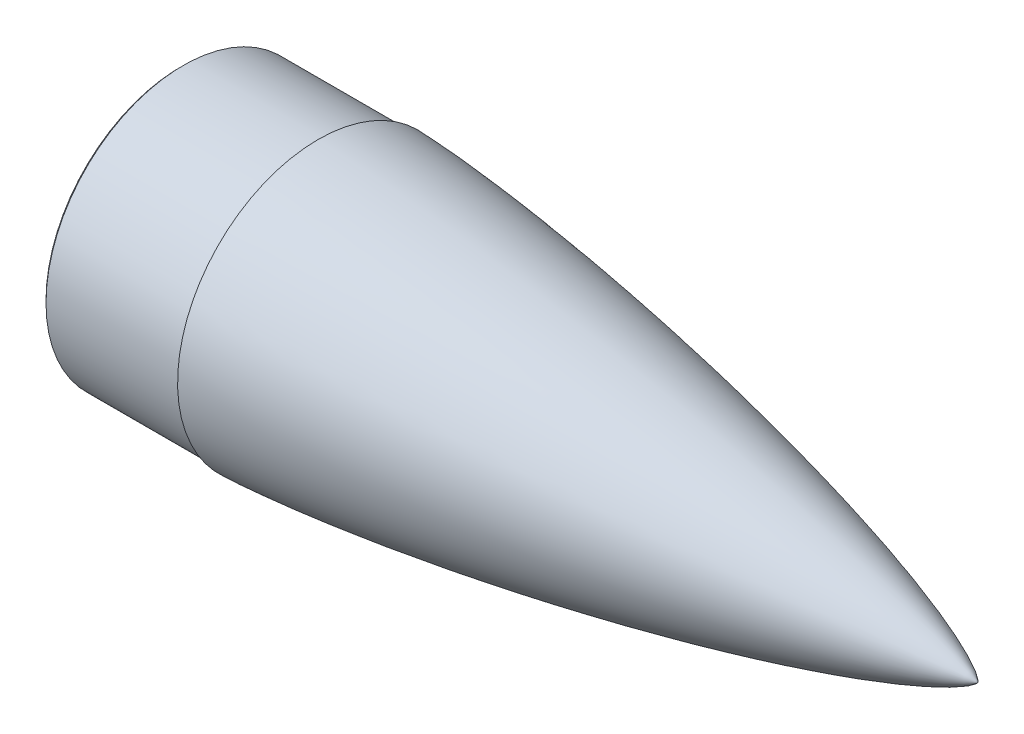
SolidWorks part; units mm, degrees
material "Plain Carbon Steel"
ref_plane "Front Plane" through (0, 0, 0) normal (0, 0, 1) x (1, 0, 0)
ref_plane "Top Plane" through (0, 0, 0) normal (0, 1, 0) x (1, 0, 0)
ref_plane "Right Plane" through (0, 0, 0) normal (1, 0, 0) x (0, 0, -1)
ref_axis "Axis1" through (46.9179, 0, 0) along (-1, 0, 0)
sketch "Sketch10" plane through (0, 0, 0) normal (0, 0, 1) x (1, 0, 0)
  line L1 (-1.0327, 0) -> (486.9547, 0) construction
  line L2 (11.1125, 81.9998) -> (11.1125, 67.4998)
  line L3 (11.1125, 81.9998) -> (-84.6045, 81.9998)
  line L4 (408.9673, 0) -> (368.9673, 0)
  line L5 (-84.6045, 81.9998) -> (-84.6045, 84.9998)
  line L6 (-84.6045, 84.9998) -> (0.3953, 84.9998)
  line L7 (0.3953, 84.9998) -> (0.3953, 86.9998)
  line L8 (11.1125, 67.4998) -> (129.3045, 67.4998)
  spline S0 degree 4 poles (408.9673, 0) (408.9649, 0.0135) (408.958, 0.0399) (408.9365, 0.0905) (408.8922, 0.1741) (408.8263, 0.2756) (408.7217, 0.4158) (408.5611, 0.6051) (408.3056, 0.8724) (407.8697, 1.2753) (407.121, 1.8851) (405.8038, 2.8259) (403.4624, 4.2872) (399.3253, 6.5318) (392.4811, 9.7589) (380.6621, 14.628) (363.6372, 20.7117) (342.2152, 27.4765) (317.4285, 34.4976) (291.8793, 41.1048) (266.2105, 47.229) (240.4455, 52.9334) (214.5989, 58.2554) (188.6809, 63.2176) (165.9462, 67.2533) (146.422, 70.4938) (130.1279, 73.0449) (117.0786, 74.9942) (104.0155, 76.8485) (92.5733, 78.3845) (82.7571, 79.6356) (74.5713, 80.6322) (68.0193, 81.4008) (61.4637, 82.1394) (54.9047, 82.8464) (48.3422, 83.5199) (41.7761, 84.1578) (36.0275, 84.6822) (31.0979, 85.1052) (26.9883, 85.4387) (23.6997, 85.6932) (20.0858, 85.9584) (16.7199, 86.189) (13.6021, 86.387) (10.7327, 86.5546) (8.4366, 86.6787) (6.14, 86.7922) (4.1299, 86.8793) (2.4065, 86.9446) (1.2573, 86.979) (0.6827, 86.9949) (0.3953, 86.9998) knots 0 0 0 0 0 0.00013 0.00026 0.00052 0.0009 0.00128 0.001925 0.002882 0.004418 0.006927 0.011111 0.018279 0.030673 0.051704 0.083102 0.139909 0.202703 0.265496 0.32829 0.391083 0.453877 0.516671 0.579464 0.642258 0.673655 0.705051 0.736448 0.767845 0.799242 0.81494 0.830639 0.846337 0.862036 0.877734 0.893432 0.909131 0.924829 0.932678 0.940527 0.948377 0.956226 0.967169 0.972641 0.978113 0.983585 0.989056 0.994528 0.997264 1 1 1 1 1 construction
  spline S1 degree 4 poles (408.9673, 0) (408.9649, 0.0135) (408.958, 0.0399) (408.9365, 0.0905) (408.8922, 0.1741) (408.8263, 0.2756) (408.7217, 0.4158) (408.5611, 0.6051) (408.3056, 0.8724) (407.8697, 1.2753) (407.121, 1.8851) (405.8038, 2.8259) (403.4624, 4.2872) (399.3253, 6.5318) (392.4811, 9.7589) (380.6621, 14.628) (363.6372, 20.7117) (342.2152, 27.4765) (317.4285, 34.4976) (291.8793, 41.1048) (266.2105, 47.229) (240.4455, 52.9334) (214.5989, 58.2554) (188.6809, 63.2176) (165.9462, 67.2533) (146.422, 70.4938) (130.1279, 73.0449) (117.0786, 74.9942) (104.0155, 76.8485) (92.5733, 78.3845) (82.7571, 79.6356) (74.5713, 80.6322) (68.0193, 81.4008) (61.4637, 82.1394) (54.9047, 82.8464) (48.3422, 83.5199) (41.7761, 84.1578) (36.0275, 84.6822) (31.0979, 85.1052) (26.9883, 85.4387) (23.6997, 85.6932) (20.0858, 85.9584) (16.7199, 86.189) (13.6021, 86.387) (10.7327, 86.5546) (8.4366, 86.6787) (6.14, 86.7922) (4.1299, 86.8793) (2.4065, 86.9446) (1.2573, 86.979) (0.6827, 86.9949) (0.3953, 86.9998) knots 0 0 0 0 0 0.00013 0.00026 0.00052 0.0009 0.00128 0.001925 0.002882 0.004418 0.006927 0.011111 0.018279 0.030673 0.051704 0.083102 0.139909 0.202703 0.265496 0.32829 0.391083 0.453877 0.516671 0.579464 0.642258 0.673655 0.705051 0.736448 0.767845 0.799242 0.81494 0.830639 0.846337 0.862036 0.877734 0.893432 0.909131 0.924829 0.932678 0.940527 0.948377 0.956226 0.967169 0.972641 0.978113 0.983585 0.989056 0.994528 0.997264 1 1 1 1 1
  spline S2 degree 4 poles (368.9673, 0) (368.9653, 0.0123) (368.9594, 0.0365) (368.9406, 0.083) (368.9023, 0.1587) (368.8455, 0.2503) (368.7557, 0.3766) (368.6167, 0.5484) (368.3929, 0.7936) (368.0087, 1.1649) (367.3447, 1.7299) (366.1761, 2.6016) (364.0928, 3.96) (360.426, 6.0407) (354.4022, 9.0183) (344.043, 13.5077) (329.152, 19.1285) (310.4252, 25.3986) (288.7413, 31.9337) (266.3785, 38.1061) (243.9014, 43.8469) (221.332, 49.212) (198.684, 54.2345) (175.9669, 58.9343) (156.0346, 62.7717) (138.9133, 65.8645) (124.6221, 68.3077) (113.1754, 70.1797) (101.7151, 71.9664) (91.6754, 73.4517) (83.0615, 74.6659) (75.8775, 75.6363) (70.1269, 76.3867) (64.3728, 77.1101) (58.6152, 77.8049) (52.854, 78.4695) (47.0892, 79.1019) (42.0417, 79.6247) (37.7129, 80.0488) (34.1039, 80.385) (31.2157, 80.6428) (28.0648, 80.911) (24.6507, 81.1843) (21.4654, 81.4195) (18.5093, 81.6177) (16.0448, 81.767) (14.3191, 81.8612) (12.8395, 81.9336) (11.8527, 81.9739) (11.3593, 81.993) (11.1125, 81.9998) knots 0 0 0 0 0 0.000135 0.00027 0.00054 0.00092 0.001299 0.001947 0.002931 0.004512 0.007081 0.01138 0.018708 0.031424 0.052705 0.084103 0.14091 0.203703 0.266497 0.329291 0.392084 0.454878 0.517672 0.580465 0.643259 0.674656 0.706052 0.737449 0.768846 0.800243 0.815941 0.831639 0.847338 0.863036 0.878735 0.894433 0.910132 0.92583 0.933679 0.941528 0.949378 0.957227 0.96792 0.978613 0.98396 0.989307 0.994653 0.997327 1 1 1 1 1 construction
  spline S3 degree 4 poles (368.9673, 0) (368.9653, 0.0123) (368.9594, 0.0365) (368.9406, 0.083) (368.9023, 0.1587) (368.8455, 0.2503) (368.7557, 0.3766) (368.6167, 0.5484) (368.3929, 0.7936) (368.0087, 1.1649) (367.3447, 1.7299) (366.1761, 2.6016) (364.0928, 3.96) (360.426, 6.0407) (354.4022, 9.0183) (344.043, 13.5077) (329.152, 19.1285) (310.4252, 25.3986) (288.7413, 31.9337) (266.3785, 38.1061) (243.9014, 43.8469) (221.332, 49.212) (198.684, 54.2345) (175.9669, 58.9343) (156.0346, 62.7717) (141.5091, 65.3956) (132.6794, 66.9245) (129.5628, 67.4559) (129.3045, 67.4998) knots 0 0 0 0 0 0.000135 0.00027 0.00054 0.00092 0.001299 0.001947 0.002931 0.004512 0.007081 0.01138 0.018708 0.031424 0.052705 0.084103 0.14091 0.203703 0.266497 0.329291 0.392084 0.454878 0.517672 0.580465 0.643259 0.674656 0.677492 0.677492 0.677492 0.677492 0.677492
  dimension "D1" = 86.9998
  dimension "D2" = 3
  dimension "D3" = 410
  dimension "D4" = 84.9998
  dimension "D5" = 370
  dimension "D6" = 84.9998
  dimension "D7" = 19.5
  dimension "D8" = 118.192
revolve "Revolve1" add sketch "Sketch10" angle 360 about axis through (46.9179, 0, 0) along (-1, 0, 0)
chamfer "Chamfer1" distance 1.5 angle 45 1 edges at (-84.6045, 0, -84.9998)
ref_plane "Plane1" through (70, 0, 0) normal (1, 0, 0) x (0, 0, -1)
ref_plane "Plane2" through (11.1125, 0, 0) normal (-1, 0, 0) x (0, 0, 1)
sketch "Sketch12" plane through (11.1125, 0, 0) normal (-1, 0, 0) x (0, 0, 1)
  line L0 (-81.9998, 0) -> (-67.4998, 0)
  circle A2 centre (0, 0) radius 81.9998 construction
  circle A3 centre (0, 0) radius 67.4998 construction
  circle A4 centre (-74.7498, 0) radius 4
  circle A5 centre (-37.3749, 64.7353) radius 4
  circle A6 centre (37.3749, 64.7353) radius 4
  circle A7 centre (74.7498, 0) radius 4
  circle A8 centre (37.3749, -64.7353) radius 4
  circle A9 centre (-37.3749, -64.7353) radius 4
  point P17 (-50.2998, -44.6412)
  point P25 (0, 0)
  dimension "D1" = 6
hole_wizard "Tapped Hole for M4x0.7 Helicoil1" positions "Sketch17" profile "Sketch18" tap size "M4x0.7" standard "Helicoil® Metric"
sketch "Sketch17" plane through (11.1125, 0, 0) normal (-1, 0, 0) x (0, 0, 1)
  point P0 (-37.3749, 64.7353)
sketch "Sketch18" plane through (11.1125, 64.7353, -37.3749) normal (0, 1, 0) x (0, 0, 1)
  line L0 (0, 0) -> (0, 31.2618)
  line L1 (0, 31.2618) -> (2.1, 30)
  line L2 (2.1, 30) -> (2.1, 0)
  line L5 (2.1, 0) -> (0, 0)
  line L10 (0, 31.2618) -> (-2.1, 30) construction
  line L11 (0, -6.35) -> (0, 107.95) construction
  dimension "Tap Drill Dia." = 4.2
  dimension "Tap Drill Depth" = 30
  dimension "Drill Angle" = 118
cosmetic thread "Hole Thread3" parameters "D1"=4.7, "D2"=5.007
pattern_circular "CirPattern1" count 6 over 360 about axis through (0, 0, 0) along (1, 0, 0) of "Tapped Hole for M4x0.7 Helicoil1"
